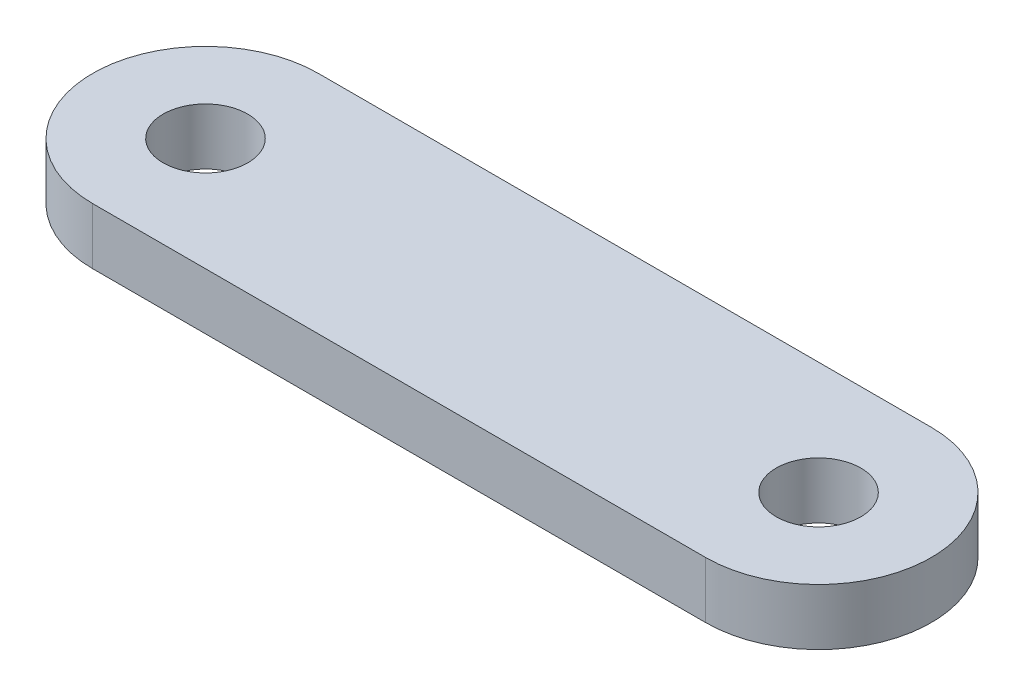
SolidWorks part; units mm, degrees
ref_plane "Front Plane" through (0, 0, 0) normal (0, 0, 1) x (1, 0, 0)
ref_plane "Top Plane" through (0, 0, 0) normal (0, 1, 0) x (1, 0, 0)
ref_plane "Right Plane" through (0, 0, 0) normal (1, 0, 0) x (0, 0, -1)
sketch "Sketch1" plane through (0, 0, 0) normal (0, 1, 0) x (1, 0, 0)
  line L0 (-13.8049, 0) -> (13.8049, 0) construction
  line L1 (-13.8049, 5.08) -> (13.8049, 5.08)
  line L2 (-13.8049, -5.08) -> (13.8049, -5.08)
  arc A0 (-13.8049, 5.08) -> (-13.8049, -5.08) centre (-13.8049, 0) ccw
  arc A1 (13.8049, -5.08) -> (13.8049, 5.08) centre (13.8049, 0) ccw
  circle A2 centre (-13.8049, 0) radius 1.905
  circle A3 centre (13.8049, 0) radius 1.905
  point P2 (0, 0)
  dimension "D2" = 3.81
  dimension "D3" = 3.175
  dimension "D1" = 27.6098
extrude "Boss-Extrude1" add sketch "Sketch1" along normal blind 2.54
